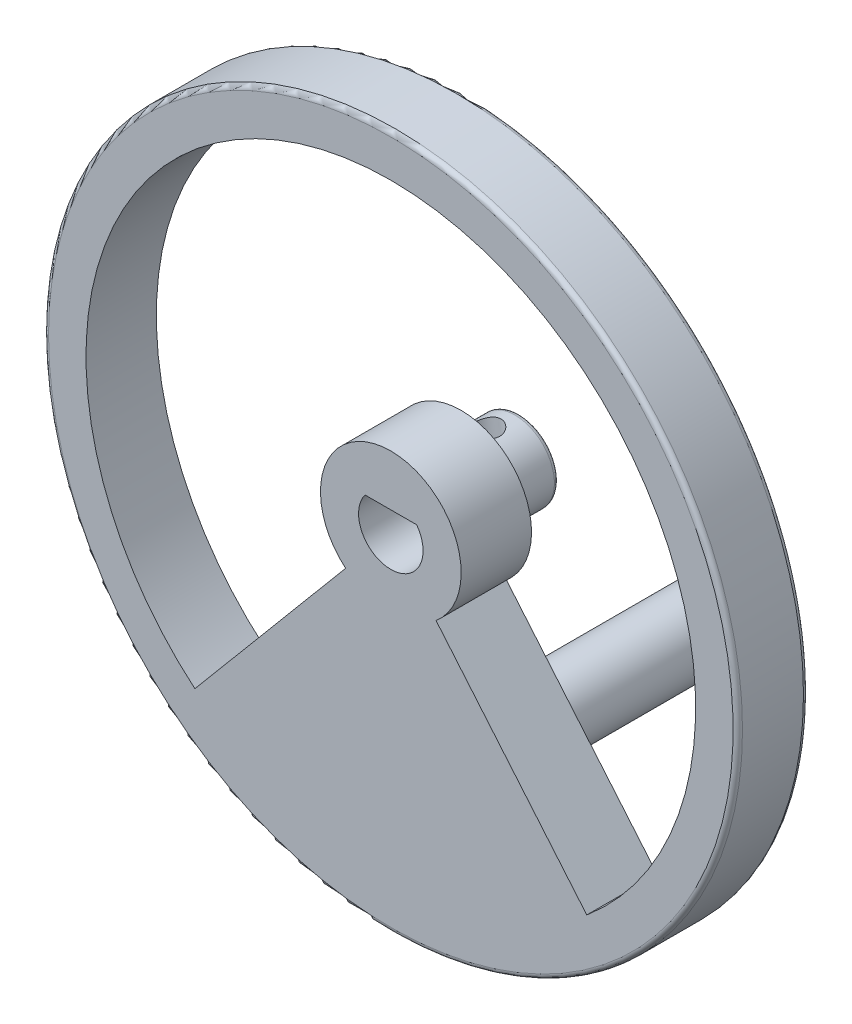
SolidWorks part; units mm, degrees
ref_plane "Front Plane" through (0, 0, 0) normal (0, 0, 1) x (1, 0, 0)
ref_plane "Top Plane" through (0, 0, 0) normal (0, 1, 0) x (1, 0, 0)
ref_plane "Right Plane" through (0, 0, 0) normal (1, 0, 0) x (0, 0, -1)
sketch "Esquisse2" plane through (0, 0, 2) normal (0, 0, -1) x (-1, 0, 0)
  circle A0 centre (0, -2) radius 14.7982
  point P2 (0, 0)
  dimension "D1" = 29.5964
extrude "Boss.-Extru.1" add sketch "Esquisse2" along normal blind 3
fillet "Congé2" radius 0.2 1 edges at (-14.7982, -2, -1)
fillet "Congé3" radius 0.2 1 edges at (-14.7982, -2, 2)
sketch "Esquisse3" plane through (0, 0, -1) normal (0, 0, -1) x (-1, 0, 0)
  circle A0 centre (0, -12) radius 1.5
  dimension "D1" = 3
extrude "Boss.-Extru.2" add sketch "Esquisse3" along normal blind 13
fillet "Congé4" radius 0.5 1 edges at (-1.5, -12, -14)
sketch "Esquisse4" plane through (0, 0, -1) normal (0, 0, -1) x (-1, 0, 0)
  line L0 (0, -3.375) -> (-2.3259, -3.375) construction
  line L2 (0, -2) -> (-0.5401, -2) construction
  line L3 (-1.1, -1.175) -> (1.1, -1.175)
  arc A1 (-1.1, -1.175) -> (1.1, -1.175) centre (0, -2) ccw
  dimension "D1" = 2.2
  dimension "D2" = 1.375
extrude "Enlèv. mat.-Extru.1" cut sketch "Esquisse4" against normal blind 3.5
sketch "Esquisse5" plane through (0, 0, -1) normal (0, 0, -1) x (-1, 0, 0)
  circle A0 centre (0, -2) radius 1.675
  dimension "D1" = 3.35
extrude "Boss.-Extru.3" add sketch "Esquisse5" along normal blind 2.5
sketch "Esquisse6" plane through (0, 0, 2) normal (0, 0, 1) x (1, 0, 0)
  line L2 (0, -2) -> (1.9962, -2) construction
  line L3 (1.1, -1.175) -> (-1.1, -1.175)
  arc A4 (-1.1, -1.175) -> (1.1, -1.175) centre (0, -2) ccw construction
  arc A6 (-1.1, -1.175) -> (1.1, -1.175) centre (0, -2) ccw
extrude "Enlèv. mat.-Extru.2" cut sketch "Esquisse6" against normal blind 5
fillet "Congé6" radius 0.2 1 edges at (-1.675, -2, -3.5)
sketch "Esquisse8" plane through (0, 0, -1) normal (0, 0, -1) x (-1, 0, 0)
  circle A0 centre (0, -12) radius 1.5 construction
  circle A1 centre (0, -12) radius 1.5
  circle A2 centre (0, -12) radius 2
  dimension "D1" = 4
extrude "Boss.-Extru.4" add sketch "Esquisse8" along normal blind 2.5
fillet "Congé7" radius 0.2 1 edges at (-2, -12, -3.5)
hole_wizard "Trou taraudé M1.61" positions "Esquisse3D2" profile "Esquisse9" tap size "M1.6" standard "ISO"
sketch3d "Esquisse3D2"
  point P0 (0.2287, -3.6593, -2.2444)
sketch "Esquisse9" plane through (0.2287, -3.6593, -2.2444) normal (0, 0, 1) x (0.9906, 0.1365, 0)
  line L0 (0, 0) -> (0, 18.3551)
  line L1 (0, 18.3551) -> (0.625, 18.3551)
  line L2 (0.625, 18.3551) -> (0.625, 0.2)
  line L3 (0.625, 0.2) -> (0.825, 0)
  line L5 (0.825, 0) -> (0, 0)
  line L6 (-0.625, 0.2) -> (-0.825, 0) construction
  line L11 (0, -6.35) -> (0, 107.95) construction
  dimension "Diamètre du trou pour taraudage jusqu'au prochain" = 1.25
  dimension "Profondeur du trou pour taraudage jusqu'au prochain" = 18.3551
  dimension "Diamètre du fraisage entrant" = 1.65
  dimension "Angle du fraisage entrant" = 90
sketch "Esquisse11" plane through (0, 0, -1) normal (0, 0, -1) x (-1, 0, 0)
  line L29 (-1.9284, -4.2981) -> (-8.3562, -11.9586)
  line L36 (0, -2) -> (-17.8468, -2) construction
  line L37 (0, -2) -> (0, -25.6256) construction
  line L40 (1.9284, -4.2981) -> (8.3562, -11.9586)
  arc A20 (8.3562, -11.9586) -> (-8.3562, -11.9586) centre (0, -2) ccw
  arc A21 (1.9284, -4.2981) -> (-1.9284, -4.2981) centre (0, -2) ccw
  dimension "D1" = 26
  dimension "D3" = 6
  dimension "D2" = 50
  dimension "D4" = 10
  dimension "D5" = 10
extrude "Enlèv. mat.-Extru.3" cut sketch "Esquisse11" against normal up to next
sketch "Esquisse14" plane through (0, 0, -14) normal (0, 0, -1) x (-1, 0, 0)
  line L0 (0, -12) -> (3.6537, -12) construction
  line L2 (2.953, -12) -> (-3.198, -12)
  line L3 (2.953, -12) -> (2.953, -10.08)
  line L4 (2.953, -10.08) -> (-3.198, -10.08)
  line L5 (-3.198, -12) -> (-3.198, -10.08)
  dimension "D1" = 6.151
  dimension "D2" = 1.92
extrude "Enlèv. mat.-Extru.4" cut sketch "Esquisse14" against normal blind 1.5
